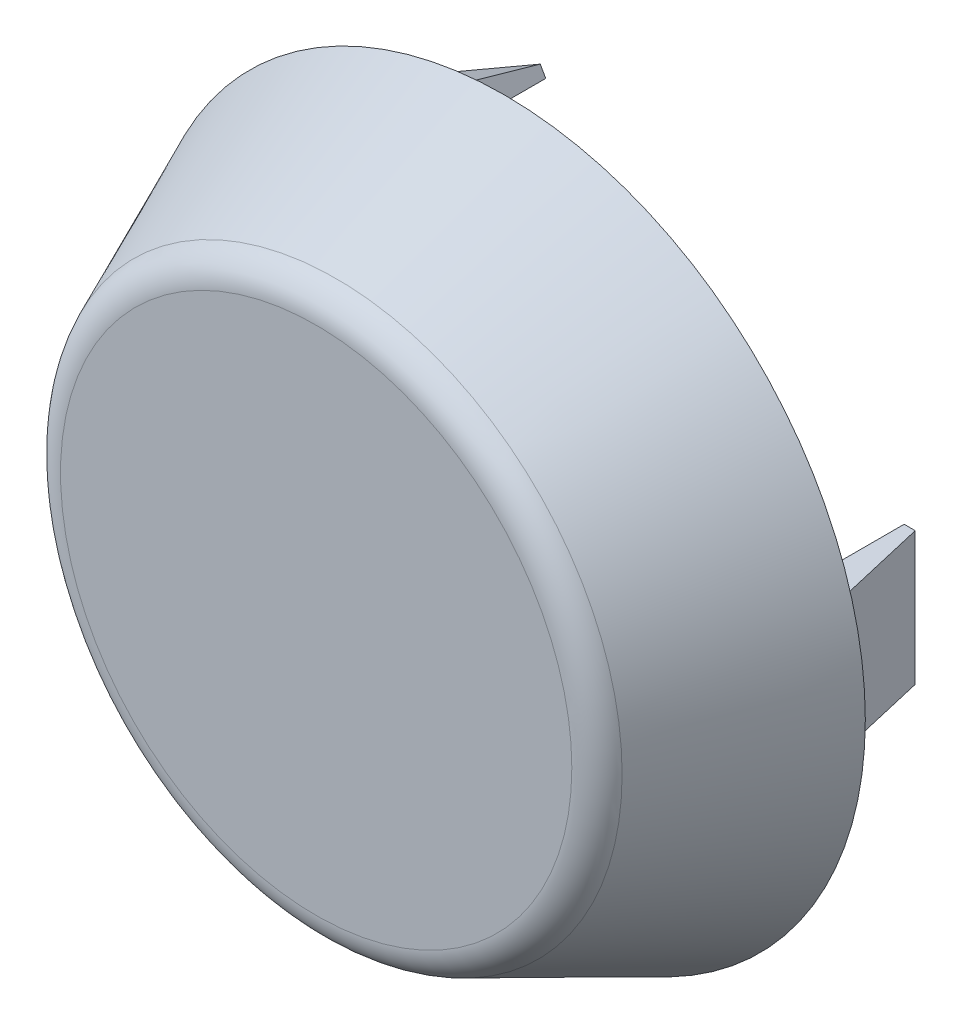
SolidWorks part; units mm, degrees
material "ABS PC"
ref_plane "Płaszczyzna przednia" through (0, 0, 0) normal (0, 0, 1) x (1, 0, 0)
ref_plane "Płaszczyzna górna" through (0, 0, 0) normal (0, 1, 0) x (1, 0, 0)
ref_plane "Płaszczyzna prawa" through (0, 0, 0) normal (1, 0, 0) x (0, 0, -1)
sketch "top" plane through (0, 0, 0) normal (0, 0, 1) x (1, 0, 0)
  circle A0 centre (0, 0) radius 12.5
  dimension "D1" = 25
ref_plane "middle-plane" through (0, 0, -8.5) normal (0, 0, 1) x (1, 0, 0)
sketch "middle" plane through (0, 0, -8.5) normal (0, 0, 1) x (1, 0, 0)
  circle A0 centre (0, 0) radius 16.25
  dimension "D1" = 32.5
ref_plane "inside-top-plane" through (0, 0, -1.5) normal (0, 0, 1) x (1, 0, 0)
sketch "inside-top" plane through (0, 0, -1.5) normal (0, 0, 1) x (1, 0, 0)
  circle A0 centre (0, 0) radius 11.25
  dimension "D1" = 22.5
loft "outside" add profiles "top" section "top" section "middle"
sketch "inside-bottom" plane through (0, 0, -8.5) normal (0, 0, 1) x (1, 0, 0)
  circle A0 centre (0, 0) radius 15
  dimension "D1" = 30
loft "inside-cutout" cut profiles "inside-top", "inside-bottom"
fillet "Zaokrąglenie1" radius 1 1 edges at (11.25, 0, -1.5)
fillet "Zaokrąglenie2" radius 1.5 1 edges at (12.5, 0, 0)
ref_plane "latches-plane" through (0, 0, -5) normal (0, 0, 1) x (1, 0, 0)
sketch "Szkic6" plane through (0, 0, -5) normal (0, 0, 1) x (1, 0, 0)
  line L0 (0, 0) -> (12.5, 0)
  line L1 (12.5, 0) -> (12.5, -3)
  line L2 (12.5, 0) -> (12.5, 3)
  line L3 (12.5, -3) -> (14, -3)
  line L4 (12.5, 3) -> (14, 3)
  line L5 (14, 3) -> (14, -3)
  dimension "D1" = 12.5
  dimension "D2" = 3
  dimension "D3" = 3
  dimension "D4" = 1.5
extrude "latch" add sketch "Szkic6" along normal blind 0.75 and the other way blind 9 contours L1 L3 L5 L4 L2
ref_plane "latch-cutout-plane" through (0, -3, 0) normal (0, -1, 0) x (-1, 0, 0)
sketch "Szkic" plane through (0, -3, 0) normal (0, -1, 0) x (-1, 0, 0)
  line L1 (-14, 14) -> (-14, 7.2266) construction
  line L2 (-14, 9.7) -> (-13, 9.7)
  line L3 (-13, 9.7) -> (-13, 8.2)
  line L4 (-13, 8.2) -> (-14, 8.2)
  line L5 (-13, 14) -> (-14, 14)
  line L6 (-12.5, 14) -> (-14, 14) construction
  line L7 (-13, 14) -> (-14, 9.7)
  line L8 (-14, 14) -> (-14.5, 14)
  line L9 (-14.5, 14) -> (-14.5, 8.2)
  line L10 (-14.5, 8.2) -> (-14, 8.2)
  dimension "D1" = 0.5
  dimension "D2" = 4.3
  dimension "D3" = 1.5
  dimension "D4" = 1
  dimension "D5" = 1.5
extrude "latch-cutout" cut sketch "Szkic" against normal blind 6
sketch "temp" plane through (0, 0, 0) normal (0, 1, 0) x (1, 0, 0)
  line L0 (0, 0) -> (0, 19.9237)
pattern_circular "Szyk kołowy2" count 3 over 360 about axis through (0, 0, 0) along (0, 0, 1) of "latch", "latch-cutout"
